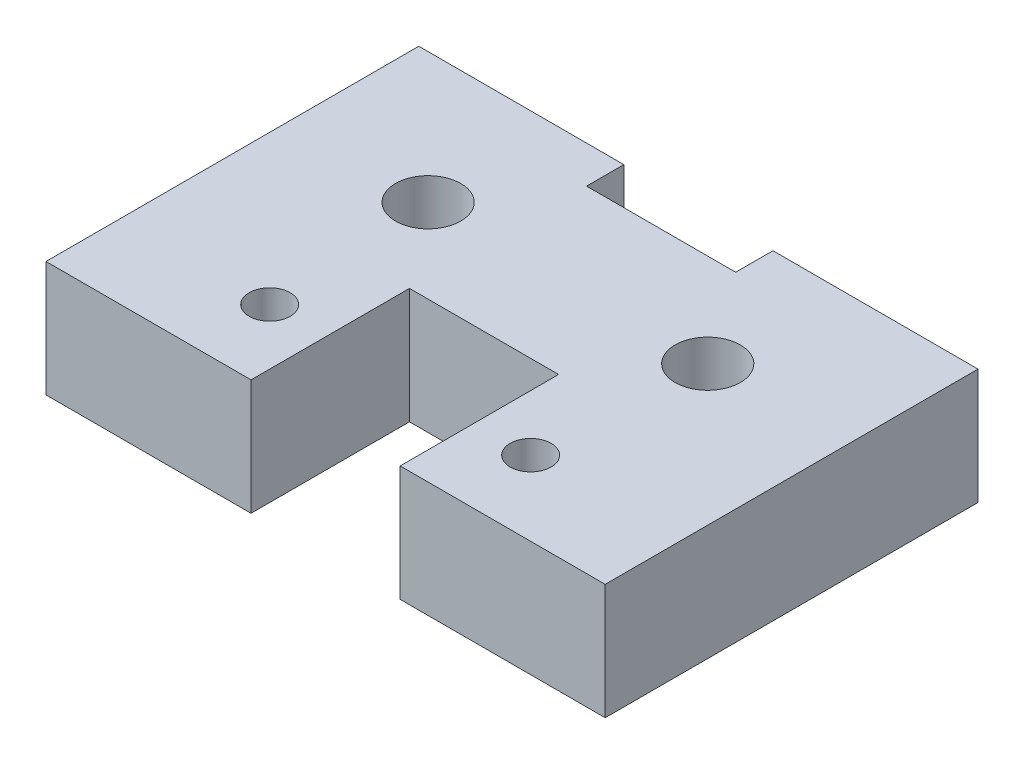
SolidWorks part; units mm, degrees
ref_plane "前视基准面" through (0, 0, 0) normal (0, 0, 1) x (1, 0, 0)
ref_plane "上视基准面" through (0, 0, 0) normal (0, 1, 0) x (1, 0, 0)
ref_plane "右视基准面" through (0, 0, 0) normal (1, 0, 0) x (0, 0, -1)
sketch "草图1" plane through (0, 0, 0) normal (0, 1, 0) x (1, 0, 0)
  line L1 (-15, -10) -> (15, -10)
  line L2 (-15, -10) -> (-15, 10)
  line L3 (-15, 10) -> (15, 10)
  line L4 (15, -10) -> (15, 10)
  line L5 (-15, -10) -> (15, 10) construction
  line L6 (-15, 10) -> (15, -10) construction
  point P0 (0, 0)
  dimension "D1" = 30
  dimension "D2" = 20
extrude "凸台-拉伸1" add sketch "草图1" along normal blind 4.2
sketch "草图2" plane through (0, 4.2, 0) normal (0, 1, 0) x (1, 0, 0)
  line L0 (0, 0) -> (0, 3) construction
  line L1 (-7.5, 3) -> (7.5, 3) construction
  line L2 (15, 10) -> (-15, 10) construction
  circle A0 centre (-7.5, 3) radius 3.05
  circle A1 centre (7.5, 3) radius 3.05
  point P7 (0, 3)
  dimension "D1" = 7
  dimension "D3" = 6.1
  dimension "D2" = 15
extrude "切除-拉伸1" cut sketch "草图2" against normal through all
sketch "草图3" plane through (0, 4.2, 0) normal (0, 1, 0) x (1, 0, 0)
  line L0 (0, 0) -> (0, -10) construction
  line L1 (-15, -10) -> (15, -10) construction
  line L2 (-7.5, 3) -> (7.5, 3) construction
  line L3 (-4, -1.5) -> (4, -1.5)
  line L4 (-4, -1.5) -> (-4, -10)
  line L5 (-4, -10) -> (4, -10)
  line L6 (4, -1.5) -> (4, -10)
  line L7 (-4, -1.5) -> (4, -10) construction
  line L8 (-4, -10) -> (4, -1.5) construction
  circle A0 centre (7.5, 3) radius 3.05 construction
  circle A1 centre (7.5, 3) radius 3.05 construction
  circle A2 centre (-7.5, 3) radius 3.05 construction
  circle A3 centre (-7.5, 3) radius 3.05 construction
  point P5 (0, -5.75)
  dimension "D1" = 4.5
  dimension "D2" = 8
extrude "切除-拉伸2" cut sketch "草图3" against normal through all
sketch "草图4" plane through (0, 4.2, 0) normal (0, 1, 0) x (1, 0, 0)
  line L8 (-4, -1.5) -> (4, -1.5)
  line L9 (4, -1.5) -> (4, -10)
  line L10 (4, -10) -> (15, -10)
  line L11 (15, -10) -> (15, 10)
  line L12 (15, 10) -> (-15, 10)
  line L13 (-15, 10) -> (-15, -10)
  line L14 (-15, -10) -> (-4, -10)
  line L15 (-4, -10) -> (-4, -1.5)
  line L16 (-4, -1.5) -> (4, -1.5)
  line L17 (4, -1.5) -> (4, -10)
  line L18 (4, -10) -> (15, -10)
  line L19 (15, -10) -> (15, 10)
  line L20 (15, 10) -> (-15, 10)
  line L21 (-15, 10) -> (-15, -10)
  line L22 (-15, -10) -> (-4, -10)
  line L23 (-4, -10) -> (-4, -1.5)
  dimension "D1" = 0
extrude "凸台-拉伸2" add sketch "草图4" along normal blind 2
sketch "草图5" plane through (0, 4.2, 0) normal (0, -1, 0) x (1, 0, 0)
  circle A0 centre (-7.5, -3) radius 1.75
  circle A1 centre (-7.5, -3) radius 3.05
  circle A2 centre (-7.5, -3) radius 3.05 construction
  circle A3 centre (7.5, -3) radius 3.05
  circle A4 centre (7.5, -3) radius 3.05 construction
  circle A5 centre (7.5, -3) radius 1.75
  dimension "D3" = 3.5
  dimension "D1" = 0
  dimension "D2" = 0
extrude "切除-拉伸3" cut sketch "草图5" against normal through all
sketch "草图6" plane through (0, 6.2, 0) normal (0, 1, 0) x (1, 0, 0)
  line L0 (0, 0) -> (0, 10) construction
  line L1 (15, 10) -> (-15, 10) construction
  line L3 (-4, 8) -> (4, 8)
  line L4 (-4, 8) -> (-4, 10)
  line L5 (-4, 10) -> (4, 10)
  line L6 (4, 8) -> (4, 10)
  line L7 (-4, 8) -> (4, 10) construction
  line L8 (-4, 10) -> (4, 8) construction
  point P5 (0, 9)
  dimension "D1" = 2
  dimension "D2" = 8
extrude "切除-拉伸4" cut sketch "草图6" against normal through all
sketch "草图7" plane through (0, 6.2, 0) normal (0, 1, 0) x (1, 0, 0)
  line L0 (-15, -10) -> (-4, -10) construction
  line L3 (-15, 10) -> (-15, -10) construction
  line L4 (0, 0) -> (0, -6.9878) construction
  circle A0 centre (-7, -6) radius 1.1
  circle A1 centre (7, -6) radius 1.1
  dimension "D3" = 2.2
  dimension "D1" = 4
  dimension "D2" = 8
extrude "切除-拉伸5" cut sketch "草图7" against normal through all
sketch "草图8" plane through (0, 0, 0) normal (0, -1, 0) x (1, 0, 0)
  line L0 (0, 0) -> (0, -5) construction
  line L2 (1.4, -3.6) -> (-1.4, -3.6)
  line L3 (1.4, -3.6) -> (1.4, -6.4)
  line L4 (1.4, -6.4) -> (-1.4, -6.4)
  line L5 (-1.4, -3.6) -> (-1.4, -6.4)
  line L6 (1.4, -3.6) -> (-1.4, -6.4) construction
  line L7 (1.4, -6.4) -> (-1.4, -3.6) construction
  line L8 (15, -10) -> (4, -10) construction
  dimension "D1" = 2.8
  dimension "D2" = 2.8
  dimension "D3" = 5
extrude "凸台-拉伸3" add sketch "草图8" along normal blind 3
sketch "草图9" plane through (0, 4.2, 0) normal (0, -1, 0) x (1, 0, 0)
  circle A0 centre (7.5, -3) radius 1.75 construction
  circle A1 centre (7.5, -3) radius 3.05
  circle A2 centre (7.5, -3) radius 3.05
  circle A3 centre (7.5, -3) radius 1.75
  circle A4 centre (-7.5, -3) radius 1.75 construction
  circle A5 centre (-7.5, -3) radius 3.05
  circle A6 centre (-7.5, -3) radius 3.05
  circle A7 centre (-7.5, -3) radius 1.75
  dimension "D1" = 0
  dimension "D2" = 0
extrude "凸台-拉伸4" add sketch "草图9" along normal blind 3.8
